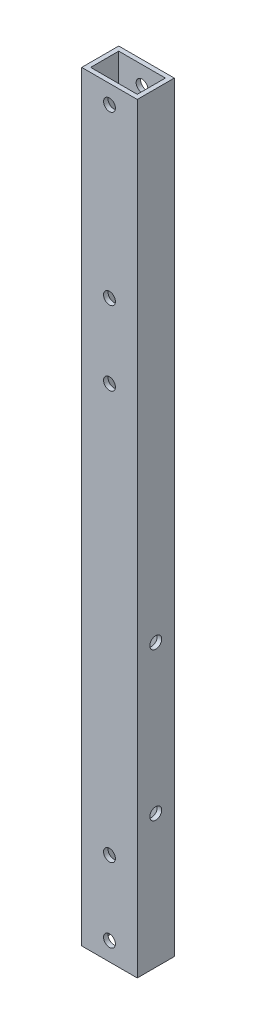
SolidWorks part; units mm, degrees
ref_plane "正面" through (0, 0, 0) normal (0, 0, 1) x (1, 0, 0)
ref_plane "平面" through (0, 0, 0) normal (0, 1, 0) x (1, 0, 0)
ref_plane "右側面" through (0, 0, 0) normal (1, 0, 0) x (0, 0, -1)
sketch "ｽｹｯﾁ1" plane through (0, 0, 0) normal (0, 1, 0) x (1, 0, 0)
  line L0 (-6.3, 3.8) -> (6.3, 3.8)
  line L1 (-7.5, 5) -> (7.5, 5)
  line L2 (-7.5, 5) -> (-7.5, -5)
  line L3 (-7.5, -5) -> (7.5, -5)
  line L4 (7.5, 5) -> (7.5, -5)
  line L5 (-7.5, 5) -> (7.5, -5) construction
  line L6 (-7.5, -5) -> (7.5, 5) construction
  line L7 (6.3, 3.8) -> (6.3, -3.8)
  line L8 (-6.3, -3.8) -> (6.3, -3.8)
  line L9 (-6.3, 3.8) -> (-6.3, -3.8)
  point P0 (0, 0)
  dimension "D1" = 15
  dimension "D2" = 10
  dimension "D3" = 1.2
extrude "ﾎﾞｽ - 押し出し1" add sketch "ｽｹｯﾁ1" along normal mid plane 220
sketch "ｽｹｯﾁ2" plane through (0, 0, -5) normal (0, 0, -1) x (-1, 0, 0)
  line L0 (0, -110) -> (0, -85) construction
  line L1 (-7.5, -110) -> (7.5, -110) construction
  circle A0 centre (0, -85) radius 1.6
  circle A1 centre (0, -105) radius 1.6
  dimension "D2" = 3.2
  dimension "D3" = 3.2
  dimension "D1" = 25
  dimension "D4" = 20
extrude "ｶｯﾄ - 押し出し1" cut sketch "ｽｹｯﾁ2" against normal blind 100
sketch "ｽｹｯﾁ3" plane through (-7.5, 0, 0) normal (-1, 0, 0) x (0, 0, 1)
  line L0 (0, -110) -> (0, 0) construction
  line L1 (-5, -110) -> (5, -110) construction
  circle A0 centre (0, -74) radius 1.6
  circle A1 centre (0, -34) radius 1.6
  dimension "D1" = 3.2
  dimension "D2" = 3.2
extrude "ｶｯﾄ - 押し出し2" cut sketch "ｽｹｯﾁ3" against normal blind 15
sketch "ｽｹｯﾁ4" plane through (0, 0, -5) normal (0, 0, -1) x (-1, 0, 0)
  line L0 (-78, 25.2765) -> (7.5, 25.2765) construction
  line L1 (7.5, 110) -> (7.5, -110) construction
  circle A0 centre (0, 25.2765) radius 1.6
  circle A1 centre (0, 45.2765) radius 1.6
  dimension "D1" = 3.2
  dimension "D2" = 3.2
  dimension "D3" = 20
extrude "ｶｯﾄ - 押し出し3" cut sketch "ｽｹｯﾁ4" against normal blind 10
sketch "ｽｹｯﾁ5" plane through (0, 110, 0) normal (0, 1, 0) x (1, 0, 0)
  line L4 (7.5, -5) -> (7.5, 5)
  line L5 (7.5, 5) -> (-7.5, 5)
  line L6 (-7.5, 5) -> (-7.5, -5)
  line L7 (-7.5, -5) -> (7.5, -5)
  line L8 (7.5, -5) -> (7.5, 5)
  line L9 (7.5, 5) -> (-7.5, 5)
  line L10 (-7.5, 5) -> (-7.5, -5)
  line L11 (-7.5, -5) -> (7.5, -5)
  dimension "D1" = 0
extrude "ｶｯﾄ - 押し出し4" cut sketch "ｽｹｯﾁ5" against normal blind 14.5
sketch "ｽｹｯﾁ6" plane through (0, 0, -5) normal (0, 0, -1) x (-1, 0, 0)
  line L0 (0, 95.5) -> (0, 90.5) construction
  line L1 (-7.5, 95.5) -> (7.5, 95.5) construction
  circle A0 centre (0, 90.5) radius 1.6
  dimension "D2" = 3.2
  dimension "D1" = 5
extrude "ｶｯﾄ - 押し出し5" cut sketch "ｽｹｯﾁ6" against normal blind 15
